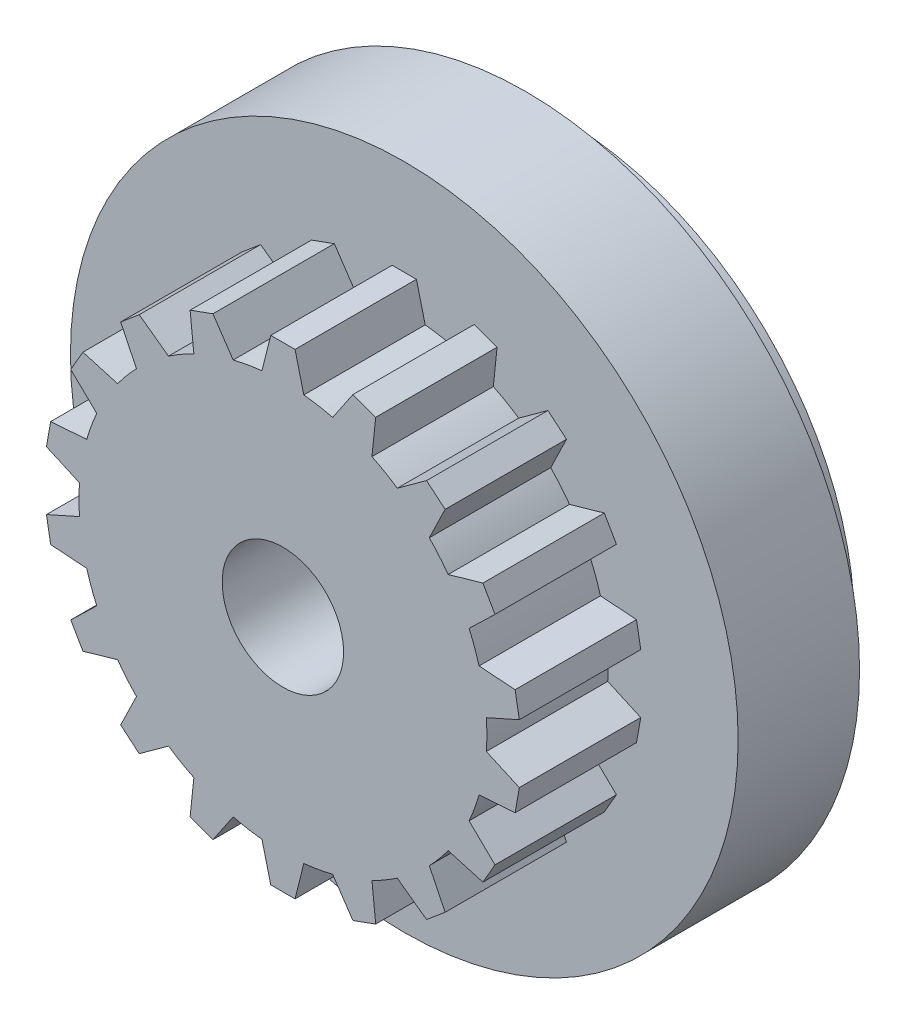
SolidWorks part; units mm, degrees
ref_plane "Front Plane" through (0, 0, 0) normal (0, 0, 1) x (1, 0, 0)
ref_plane "Top Plane" through (0, 0, 0) normal (0, 1, 0) x (1, 0, 0)
ref_plane "Right Plane" through (0, 0, 0) normal (1, 0, 0) x (0, 0, -1)
sketch "Sketch1" plane through (0, 0, 0) normal (0, 0, 1) x (1, 0, 0)
  circle A0 centre (0, 0) radius 10.668
  circle A1 centre (0, 0) radius 3.175
  dimension "D1" = 21.336
  dimension "D2" = 6.35
extrude "Boss-Extrude1" add sketch "Sketch1" along normal blind 6.35
sketch "Sketch2" plane through (0, 0, 6.35) normal (0, 0, 1) x (1, 0, 0)
  line L0 (0, 0) -> (0, 12.446) construction
  line L1 (-0.635, 12.446) -> (0.635, 12.446)
  line L2 (-1.27, 9.906) -> (1.27, 9.906)
  line L3 (-0.635, 12.446) -> (-1.27, 9.906)
  line L4 (0.635, 12.446) -> (1.27, 9.906)
  line L81 (4.8535, 11.4782) -> (4.5815, 8.8742)
  line L82 (3.6601, 11.9126) -> (2.1946, 9.743)
  line L83 (2.1946, 9.743) -> (4.5815, 8.8742)
  line L84 (3.6601, 11.9126) -> (4.8535, 11.4782)
  line L85 (8.4866, 9.126) -> (7.3403, 6.7721)
  line L86 (7.5137, 9.9424) -> (5.3946, 8.4048)
  line L87 (5.3946, 8.4048) -> (7.3403, 6.7721)
  line L88 (7.5137, 9.9424) -> (8.4866, 9.126)
  line L89 (11.0961, 5.6731) -> (9.2138, 3.8531)
  line L90 (10.4611, 6.7729) -> (7.9438, 6.0529)
  line L91 (7.9438, 6.0529) -> (9.2138, 3.8531)
  line L92 (10.4611, 6.7729) -> (11.0961, 5.6731)
  line L93 (12.3672, 1.5359) -> (9.976, 0.4695)
  line L94 (12.1467, 2.7866) -> (9.535, 2.9709)
  line L95 (9.535, 2.9709) -> (9.976, 0.4695)
  line L96 (12.1467, 2.7866) -> (12.3672, 1.5359)
  line L97 (12.1467, -2.7866) -> (9.535, -2.9709)
  line L98 (12.3672, -1.5359) -> (9.976, -0.4695)
  line L99 (9.976, -0.4695) -> (9.535, -2.9709)
  line L100 (12.3672, -1.5359) -> (12.1467, -2.7866)
  line L101 (10.4611, -6.7729) -> (7.9438, -6.0529)
  line L102 (11.0961, -5.6731) -> (9.2138, -3.8531)
  line L103 (9.2138, -3.8531) -> (7.9438, -6.0529)
  line L104 (11.0961, -5.6731) -> (10.4611, -6.7729)
  line L105 (7.5137, -9.9424) -> (5.3946, -8.4048)
  line L106 (8.4866, -9.126) -> (7.3403, -6.7721)
  line L107 (7.3403, -6.7721) -> (5.3946, -8.4048)
  line L108 (8.4866, -9.126) -> (7.5137, -9.9424)
  line L109 (3.6601, -11.9126) -> (2.1946, -9.743)
  line L110 (4.8535, -11.4782) -> (4.5815, -8.8742)
  line L111 (4.5815, -8.8742) -> (2.1946, -9.743)
  line L112 (4.8535, -11.4782) -> (3.6601, -11.9126)
  line L113 (-0.635, -12.446) -> (-1.27, -9.906)
  line L114 (0.635, -12.446) -> (1.27, -9.906)
  line L115 (1.27, -9.906) -> (-1.27, -9.906)
  line L116 (0.635, -12.446) -> (-0.635, -12.446)
  line L117 (-4.8535, -11.4782) -> (-4.5815, -8.8742)
  line L118 (-3.6601, -11.9126) -> (-2.1946, -9.743)
  line L119 (-2.1946, -9.743) -> (-4.5815, -8.8742)
  line L120 (-3.6601, -11.9126) -> (-4.8535, -11.4782)
  line L121 (-8.4866, -9.126) -> (-7.3403, -6.7721)
  line L122 (-7.5137, -9.9424) -> (-5.3946, -8.4048)
  line L123 (-5.3946, -8.4048) -> (-7.3403, -6.7721)
  line L124 (-7.5137, -9.9424) -> (-8.4866, -9.126)
  line L125 (-11.0961, -5.6731) -> (-9.2138, -3.8531)
  line L126 (-10.4611, -6.7729) -> (-7.9438, -6.0529)
  line L127 (-7.9438, -6.0529) -> (-9.2138, -3.8531)
  line L128 (-10.4611, -6.7729) -> (-11.0961, -5.6731)
  line L129 (-12.3672, -1.5359) -> (-9.976, -0.4695)
  line L130 (-12.1467, -2.7866) -> (-9.535, -2.9709)
  line L131 (-9.535, -2.9709) -> (-9.976, -0.4695)
  line L132 (-12.1467, -2.7866) -> (-12.3672, -1.5359)
  line L133 (-12.1467, 2.7866) -> (-9.535, 2.9709)
  line L134 (-12.3672, 1.5359) -> (-9.976, 0.4695)
  line L135 (-9.976, 0.4695) -> (-9.535, 2.9709)
  line L136 (-12.3672, 1.5359) -> (-12.1467, 2.7866)
  line L137 (-10.4611, 6.7729) -> (-7.9438, 6.0529)
  line L138 (-11.0961, 5.6731) -> (-9.2138, 3.8531)
  line L139 (-9.2138, 3.8531) -> (-7.9438, 6.0529)
  line L140 (-11.0961, 5.6731) -> (-10.4611, 6.7729)
  line L141 (-7.5137, 9.9424) -> (-5.3946, 8.4048)
  line L142 (-8.4866, 9.126) -> (-7.3403, 6.7721)
  line L143 (-7.3403, 6.7721) -> (-5.3946, 8.4048)
  line L144 (-8.4866, 9.126) -> (-7.5137, 9.9424)
  line L145 (-3.6601, 11.9126) -> (-2.1946, 9.743)
  line L146 (-4.8535, 11.4782) -> (-4.5815, 8.8742)
  line L147 (-4.5815, 8.8742) -> (-2.1946, 9.743)
  line L148 (-4.8535, 11.4782) -> (-3.6601, 11.9126)
  point P6 (0, 12.446)
  point P9 (0, 9.906)
  point P79 (0, 0)
  dimension "D1" = 1.27
  dimension "D2" = 2.54
  dimension "D3" = 2.54
  dimension "D4" = 12.446
  dimension "D5" = 18
extrude "Boss-Extrude2" add sketch "Sketch2" against normal up to surface (6.35 mm away) up to face at (10.668, 0, 0)
sketch "Sketch3" plane through (0, 0, 0) normal (0, 0, -1) x (-1, 0, 0)
  circle A0 centre (0, 0) radius 17.4625
  dimension "D1" = 34.925
extrude "Boss-Extrude3" add sketch "Sketch3" along normal blind 6.35
sketch "Sketch4" plane through (0, 0, 0) normal (0, 0, 1) x (1, 0, 0)
  circle A0 centre (0, 0) radius 1.5875
  dimension "D1" = 3.175
extrude "Cut-Extrude1" cut sketch "Sketch4" against normal blind 6.35
sketch "Sketch5" plane through (0, 0, -6.35) normal (0, 0, -1) x (-1, 0, 0)
  circle A0 centre (0, 0) radius 15.24
  circle A1 centre (0, 0) radius 1.5875
  dimension "D1" = 30.48
extrude "Boss-Extrude4" add sketch "Sketch5" along normal blind 1.9507 separate body
